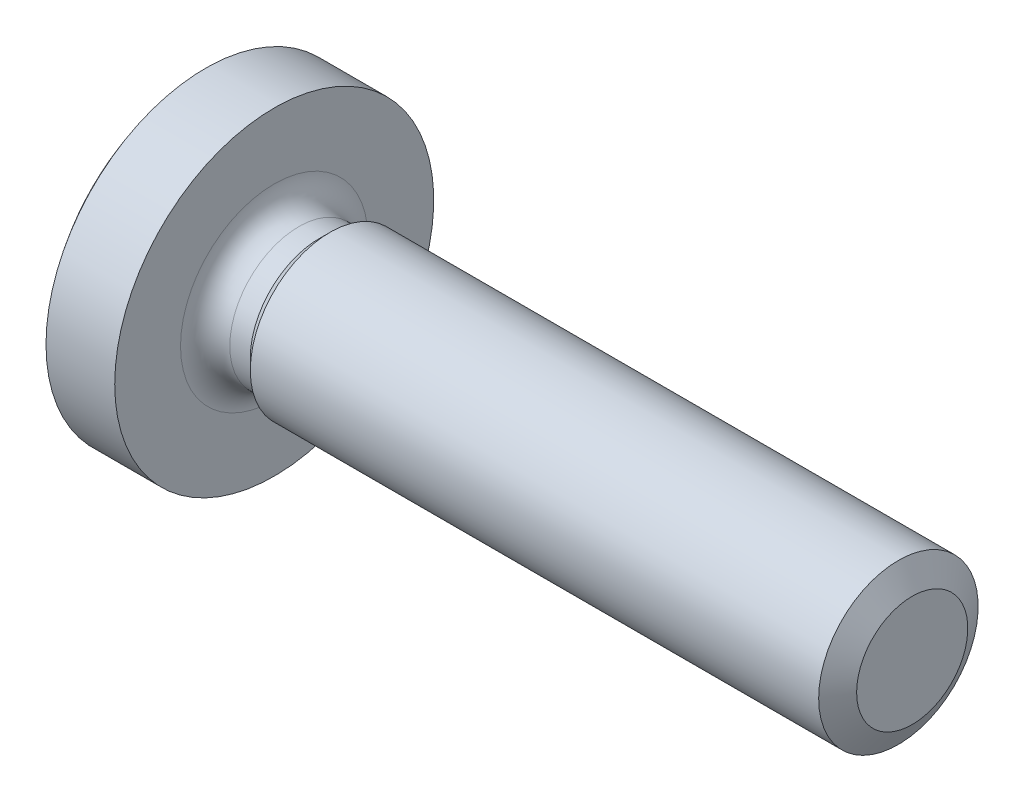
SolidWorks part; units mm, degrees
revolve "基体-旋转" add sketch "草图2" angle 360 about L0
sketch "草图2" plane through (0, 0, 0) normal (0, 0, 1) x (1, 0, 0)
  line L0 (-1.3318, 0) -> (6.5885, 0) construction
  line L1 (0, 0) -> (19.1, 0)
  line L2 (19.1, 0) -> (19.1, 2)
  line L3 (19.1, 2) -> (4.5, 2)
  line L4 (4.5, 2) -> (4.232, 1.732)
  line L5 (4.232, 1.732) -> (3.718, 1.732)
  line L6 (3.1, 2.35) -> (3.1, 4)
  line L7 (3.1, 4) -> (1.3765, 4)
  arc A0 (3.1, 2.35) -> (3.718, 1.732) centre (3.718, 2.35) ccw
  arc A1 (0, 0) -> (1.3765, 4) centre (6.5, 0) cw
  dimension "D3" = 6.5
  dimension "dk" = 8
  dimension "d" = 4
  dimension "l" = 16
  dimension "a" = 1.4
  dimension "D1" = 45
  dimension "D2" = 3.464
  dimension "da" = 4.7
  dimension "k" = 3.1
cosmetic thread "装饰螺纹线1" parameters "D1"=14.6, "D2"=3.464
ref_plane "前视" through (0, 0, 0) normal (0, 0, 1) x (1, 0, 0)
ref_plane "上视" through (0, 0, 0) normal (0, 1, 0) x (1, 0, 0)
ref_plane "右视" through (0, 0, 0) normal (1, 0, 0) x (0, 0, -1)
sketch "尺寸草图" plane through (0, 0, 0) normal (0, 0, 1) x (1, 0, 0)
  line L0 (0, 0) -> (16, 0)
  line L1 (0, 0) -> (0, 8)
  line L2 (16, 0) -> (16, 4.7)
  point P5 (0, 4)
  point P6 (15.3, 0)
  point P7 (1.4, 0)
  point P8 (3.1, 0)
  point P9 (9.5, 0)
  point P10 (4.4, 0)
  point P11 (13.6, 0)
  dimension "dk" = 8
  dimension "d" = 4
  dimension "l" = 16
  dimension "a" = 1.4
  dimension "da" = 4.7
  dimension "k" = 3.1
  dimension "P" = 0.7
  dimension "rf" = 6.5
  dimension "m" = 4.4
  dimension "h" = 2.4
sketch "草图3" plane through (0, 0, 0) normal (0, 0, 1) x (1, 0, 0)
  line L0 (18.7538, 2) -> (19.4538, 2)
  line L1 (19.4538, 2) -> (19.1, 1.3938)
  line L2 (19.1, 1.3938) -> (18.7538, 2)
  line L3 (19.1, 2) -> (4.5, 2) construction
  line L4 (19.1, -2) -> (19.1, 2) construction
  line L5 (-0.2428, 0) -> (7.1644, 0) construction
  line L6 (-1.3318, 0) -> (6.5885, 0) construction
  dimension "P" = 0.7
  dimension "D1" = 0.6062
  dimension "D2" = 60
revolve "切除-旋转1" cut sketch "草图3" angle 360 about L5
sketch "草图5" plane through (0, 0, 0) normal (1, 0, 0) x (0, 0, -1)
  line L1 (0.35, 2.2) -> (-0.35, 2.2)
  line L2 (0.35, 2.2) -> (0.35, -2.2)
  line L3 (0.35, -2.2) -> (-0.35, -2.2)
  line L4 (-0.35, 2.2) -> (-0.35, -2.2)
  point P4 (0.35, 0)
  point P5 (0, 2.2)
  dimension "m" = 4.4
  dimension "D1" = 0.7
ref_plane "基准面1" through (2.4, 0, 0) normal (1, 0, 0) x (0, 0, -1)
pattern_linear "阵列(线性)1" [suppressed] count 22 spacing 0.7 along (1, 0, 0)
sketch "草图6" plane through (2.4, 0, 0) normal (1, 0, 0) x (0, 0, -1)
  point P0 (0, 0)
loft "切除-放样1" cut profiles "草图6", "草图5"
ref_plane "基准面2" through (0, 0, 0) normal (0, -0.7071, 0.7071) x (1, 0, 0)
mirror "镜向1" about plane through (0, 0, 0) normal (0, -0.7071, 0.7071) of "切除-放样1"
equation "\"l@草图2\" = \"l@尺寸草图\""
equation "\"dk@草图2\" = \"dk@尺寸草图\""
equation "\"k@草图2\" = \"k@尺寸草图\""
equation "\"D2@草图2\" = \"d@尺寸草图\"*0.866"
equation "\"a@草图2\" = \"a@尺寸草图\""
equation "\"D3@草图2\" = \"rf@尺寸草图\""
equation "\"d@草图2\" = \"d@尺寸草图\""
equation "\"da@草图2\" = \"da@尺寸草图\""
equation "\"D2@装饰螺纹线1\" = \"d@尺寸草图\"*0.866"
equation "\"D1@装饰螺纹线1\" = \"l@尺寸草图\"-\"a@尺寸草图\""
equation "\"P@草图3\" = \"P@尺寸草图\""
equation "\"D1@草图3\" = \"P@尺寸草图\"*0.866"
equation "\"h@基准面1\" = \"h@尺寸草图\""
equation "\"D1@草图5\" = \"P@尺寸草图\""
equation "\"m@草图5\" = \"m@尺寸草图\""
equation "\"D3@阵列(线性)1\" = \"P@尺寸草图\""
equation "\"D1@阵列(线性)1\" = (\"l@尺寸草图\"-\"a@尺寸草图\")/\"P@尺寸草图\"+1"
